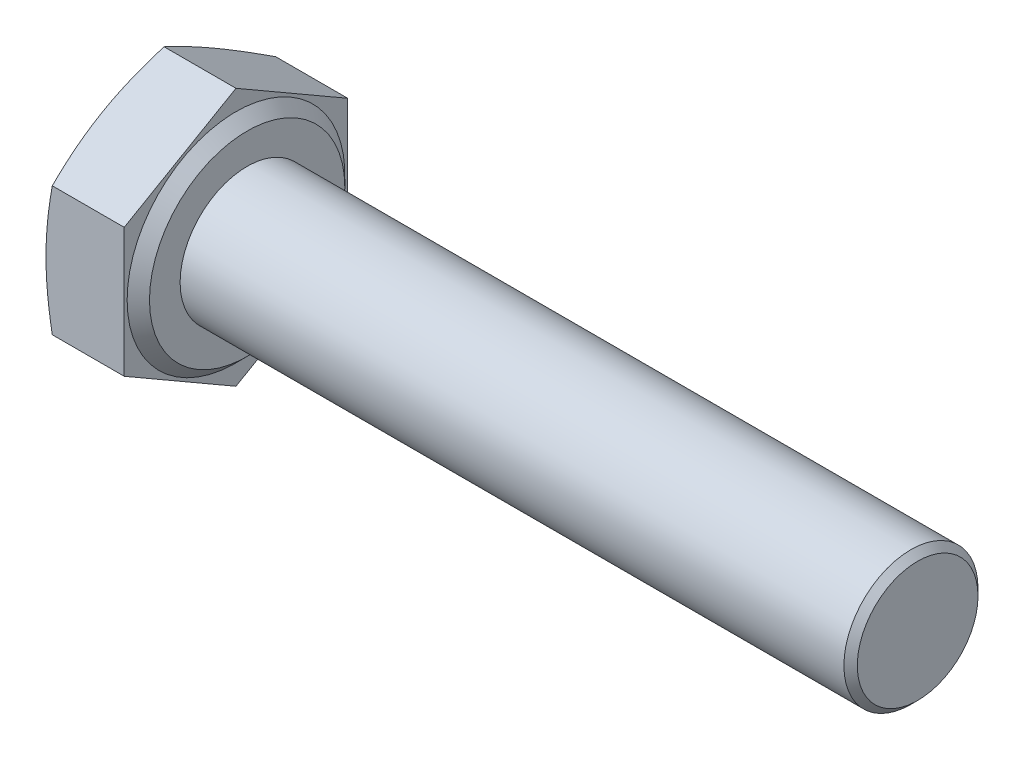
SolidWorks part; units mm, degrees
ref_plane "Front" through (0, 0, 0) normal (0, 0, 1) x (1, 0, 0)
ref_plane "Top" through (0, 0, 0) normal (0, 1, 0) x (1, 0, 0)
ref_plane "Right" through (0, 0, 0) normal (1, 0, 0) x (0, 0, -1)
sketch "Sketch2" plane through (0, 0, 0) normal (1, 0, 0) x (0, 0, -1)
  line L1 (0, -5.7735) -> (5, -2.8868)
  line L2 (5, -2.8868) -> (5, 2.8868)
  line L3 (5, 2.8868) -> (0, 5.7735)
  line L4 (0, 5.7735) -> (-5, 2.8868)
  line L5 (-5, 2.8868) -> (-5, -2.8868)
  line L6 (-5, -2.8868) -> (0, -5.7735)
  circle A0 centre (0, 0) radius 5 construction
  dimension "s" = 10
extrude "BaseHead" add sketch "Sketch2" along normal blind 4
sketch "Sketch3" plane through (0, 0, 0) normal (0, 0, 1) x (1, 0, 0)
  line L0 (4, 5.7735) -> (4, 4.37)
  line L2 (4, 4.37) -> (3.5, 4.87)
  line L3 (3.5, 4.87) -> (3.5, 5.7735)
  line L5 (3.5, 5.7735) -> (4, 5.7735)
  line L6 (-0.9571, 0) -> (7.6478, 0) construction
  line L7 (4, 5.7735) -> (0, 5.7735) construction
  dimension "D1" = 45
  dimension "c" = 0.5
  dimension "dw" = 8.74
revolve "BearingFace" cut sketch "Sketch3" angle 360 about L6
sketch "Sketch4" plane through (0, 0, 0) normal (0, 0, 1) x (1, 0, 0)
  line L0 (-0.4935, 0) -> (3.5626, 0) construction
  line L2 (0, 5.7735) -> (0.2815, 5.7735)
  line L4 (0.2815, 5.7735) -> (0, 5)
  line L6 (0, 5) -> (0, 5.7735)
  line L7 (3.5, 5.7735) -> (0, 5.7735) construction
  dimension "D1" = 20
  dimension "D2" = 10
revolve "HeadChamfer" cut sketch "Sketch4" angle 360 about L0
sketch "Sketch5" plane through (4, 0, 0) normal (1, 0, 0) x (0, 0, -1)
  circle A0 centre (0, 0) radius 3
  dimension "d" = 6
extrude "BaseBody" add sketch "Sketch5" along normal blind 30
cosmetic thread "ThreadCosmetic1" [suppressed] parameters "D2"=4.917
chamfer "Chamfer1" distance 0.3 angle 45 1 edges at (34, 0, -3)
fillet "HeadFillet" [suppressed] radius 0.25
sketch "Sketch6" plane through (0, 0, 0) normal (0, 0, 1) x (1, 0, 0)
  line L0 (4, 3.5415) -> (4.5415, 3.5415)
  line L1 (4.5415, 3.5415) -> (4.5415, 3)
  line L2 (4.5415, 3) -> (4.2708, 2.531)
  line L3 (4.2708, 2.531) -> (4, 3)
  line L4 (4, 3) -> (4, 3.5415)
  line L5 (4, -4.37) -> (4, 4.37) construction
  line L6 (33.7, 3) -> (4, 3) construction
  dimension "D1" = 0.5415
revolve "Cut-Revolve10" [suppressed] cut sketch "Sketch6" angle 360
pattern_linear "LPattern10" [suppressed] count 46
scale "缩放比例1" scale about origin uniform scaling yes scale factor 0.25
equation "\"D2@Sketch4\" = \"s@Sketch2\""
equation "\"D1@Chamfer1\" = 0.05 * \"d@Sketch5\""
equation "\"D1@Sketch6\" =  ( \"d@Sketch5\" - \"D2@ThreadCosmetic1\" )  / 2"
equation "\"pitch@LPattern10\" = 1.2 * \"D1@Sketch6\""
equation "\"D1@LPattern10\" = (  \"l@BaseBody\"-\"D1@Chamfer1\" )  / \"pitch@LPattern10\""
